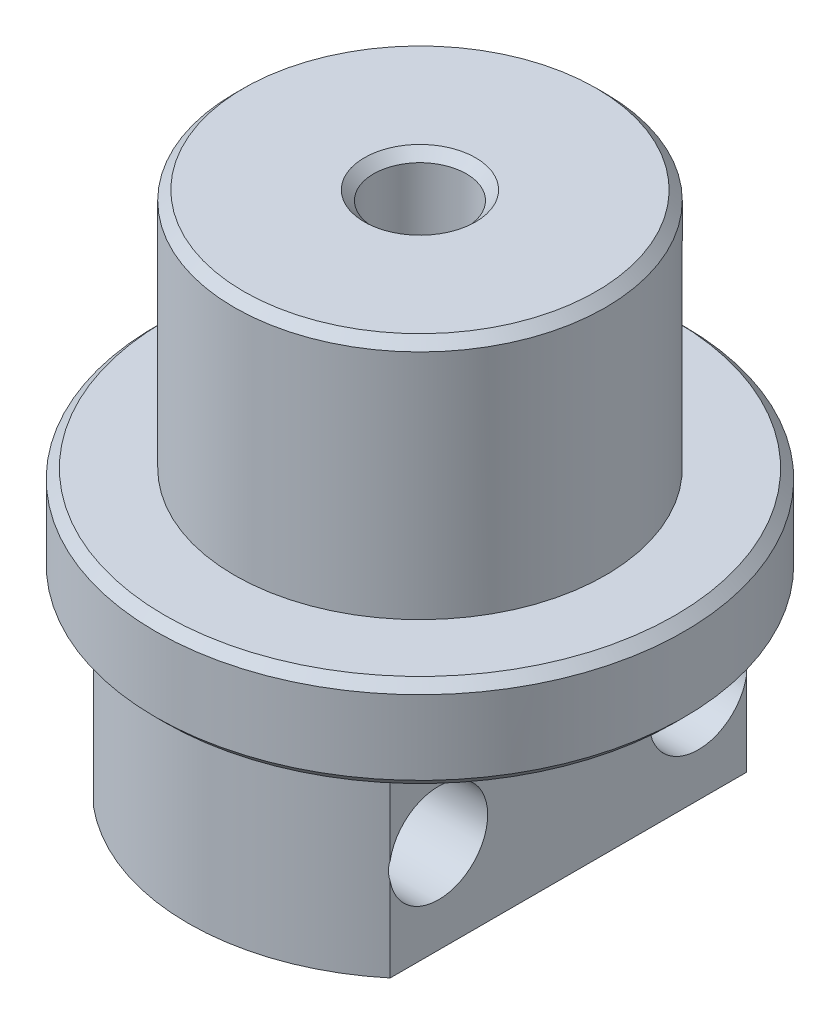
SolidWorks part; units mm, degrees
ref_plane "Płaszczyzna przednia" through (0, 0, 0) normal (0, 0, 1) x (1, 0, 0)
ref_plane "Płaszczyzna górna" through (0, 0, 0) normal (0, 1, 0) x (1, 0, 0)
ref_plane "Płaszczyzna prawa" through (0, 0, 0) normal (1, 0, 0) x (0, 0, -1)
sketch "Szkic1" plane through (0, 0, 0) normal (0, 0, 1) x (1, 0, 0)
  line L0 (0, 0) -> (0, 28)
  line L1 (0, 28) -> (10, 28)
  line L2 (10, 28) -> (10, 15)
  line L3 (10, 15) -> (14.25, 15)
  line L4 (14.25, 15) -> (14.25, 10)
  line L5 (14.25, 10) -> (12.5, 10)
  line L6 (12.5, 10) -> (12.5, 0)
  line L7 (12.5, 0) -> (0, 0)
  line L8 (0, 0) -> (0, -3.9362) construction
  dimension "D1" = 20
  dimension "D2" = 28.5
  dimension "D3" = 13
  dimension "D4" = 5
  dimension "D5" = 10
  dimension "D6" = 25
revolve "Obrót1" add sketch "Szkic1" angle 360 about L8
sketch "Szkic2" plane through (0, 0, 0) normal (0, -1, 0) x (-1, 0, 0)
  line L0 (-8, -9.6047) -> (-8, 9.6047)
  line L1 (8, -9.6047) -> (8, 9.6047)
  line L2 (8, 60) -> (8, -60) construction
  circle A0 centre (0, 0) radius 12.5 construction
  arc A1 (-8, 9.6047) -> (-8, -9.6047) centre (0, 0) ccw
  arc A2 (8, -9.6047) -> (8, 9.6047) centre (0, 0) ccw
extrude "Wytnij-wyciągnięcie1" cut sketch "Szkic2" against normal up to surface (10 mm away) up to face at (0, 10, 14.25)
hole_wizard "Pogłębienie walcowe pod M5 Śrubę z łbem walcowym z gniazdem" positions "Szkic3" profile "Szkic4" counterbore size "M5" standard "Ansi Metric"
sketch "Szkic3" plane through (24.5, 33, -156.3495) normal (1, 0, 0) x (0, 0, -1)
  line L1 (-172.4952, -57.5) -> (-140.2039, -57.5) construction
  line L2 (-156.3495, -57.5) -> (-156.3495, -22.6678) construction
  point P0 (-163.3495, -28)
  point P3 (-149.3495, -28)
sketch "Szkic4" plane through (24.5, 5, 7) normal (0, 1, 0) x (0, 0, -1)
  line L0 (0, 0) -> (0, 61.5923)
  line L1 (0, 61.5923) -> (2.65, 60)
  line L2 (2.65, 60) -> (2.65, 5)
  line L3 (2.65, 5) -> (5, 5)
  line L4 (5, 5) -> (5, 0)
  line L5 (5, 0) -> (0, 0)
  line L6 (0, 61.5923) -> (-2.65, 60) construction
  line L7 (0, -6.35) -> (0, 107.95) construction
  dimension "Średnica otworu" = 5.3
  dimension "Głębokość otworu" = 60
  dimension "Średnica pogłębienia walcowego" = 10
  dimension "Głębokość pogłębienia walcowego" = 5
  dimension "Kąt wiertła" = 118
hole_wizard "Otwory ustalające Ø5.0mm1" positions "Szkic6" profile "Szkic8" hole size "Ø5.0" standard "Ansi Metric" end condition through all
sketch "Szkic6" plane through (0, 28, 0) normal (0, 1, 0) x (1, 0, 0)
  point P0 (0, 0)
sketch "Szkic8" plane through (0, 28, 0) normal (1, 0, 0) x (0, 0, 1)
  line L0 (0, 0) -> (0, 28)
  line L1 (0, 28) -> (2.5, 28)
  line L2 (2.5, 28) -> (2.5, 0)
  line L5 (2.5, 0) -> (0, 0)
  line L11 (0, -6.35) -> (0, 107.95) construction
  dimension "Średnica otworu na wylot" = 5
  dimension "Głębokość otworu na wylot" = 28
chamfer "Sfazowanie1" distance 0.5 angle 45 4 edges at (0, 10, 14.25) (0, 15, 14.25) (0, 28, 10) (0, 28, 2.5)
